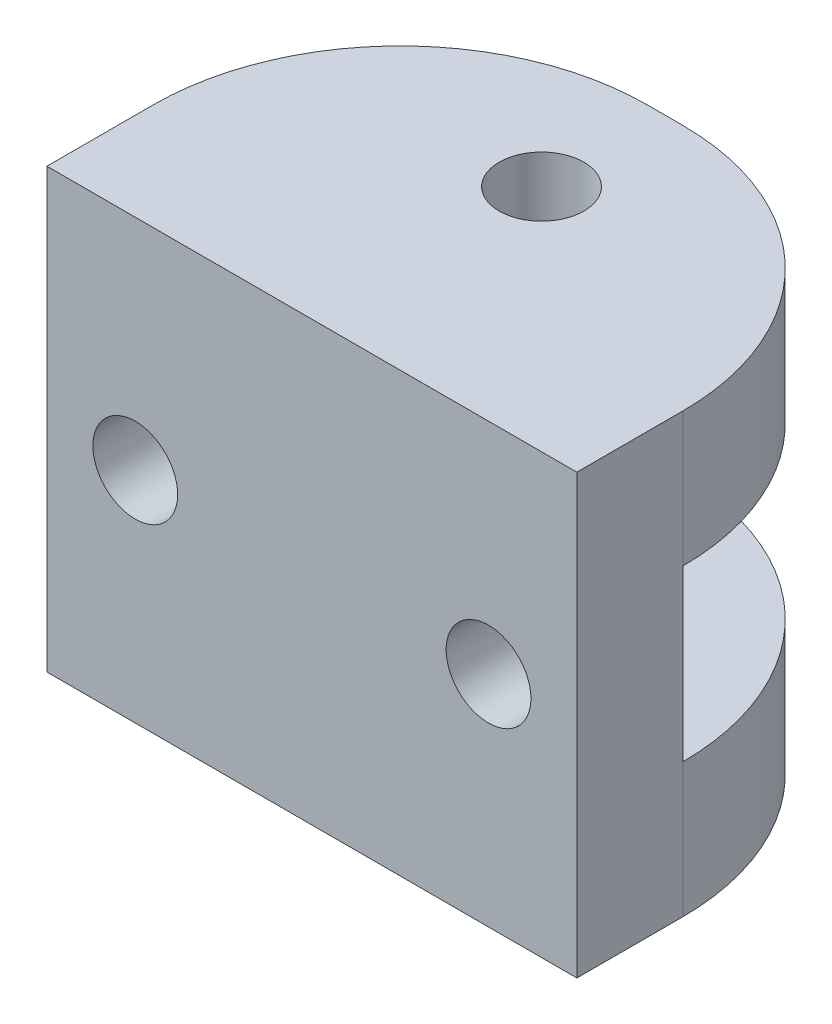
SolidWorks part; units mm, degrees
ref_plane "Front Plane" through (0, 0, 0) normal (0, 0, 1) x (1, 0, 0)
ref_plane "Top Plane" through (0, 0, 0) normal (0, 1, 0) x (1, 0, 0)
ref_plane "Right Plane" through (0, 0, 0) normal (1, 0, 0) x (0, 0, -1)
sketch "Sketch1" plane through (0, 0, 0) normal (1, 0, 0) x (0, 0, -1)
  line L0 (50, 62) -> (50, 43)
  line L1 (0, 0) -> (50, 0)
  line L2 (0, 0) -> (0, 62)
  line L3 (0, 62) -> (50, 62)
  line L5 (50, 43) -> (15, 43)
  line L6 (15, 43) -> (15, 19)
  line L7 (15, 19) -> (50, 19)
  line L8 (50, 19) -> (50, 0)
  dimension "D1" = 24
  dimension "D2" = 62
  dimension "D3" = 35
  dimension "D4" = 50
extrude "Boss-Extrude1" add sketch "Sketch1" along normal blind 75
sketch "Sketch2" plane through (0, 0, 0) normal (0, 0, 1) x (1, 0, 0)
  line L0 (0, 31) -> (75, 31) construction
  line L1 (0, 62) -> (0, 0) construction
  line L2 (75, 62) -> (75, 0) construction
  circle A0 centre (62.5, 31) radius 6
  circle A1 centre (12.5, 31) radius 6
  point P10 (37.5, 31)
  dimension "D3" = 12
  dimension "D1" = 50
  dimension "D2" = 25
extrude "Cut-Extrude1" cut sketch "Sketch2" against normal through all
sketch "Sketch3" plane through (0, 62, 0) normal (0, 1, 0) x (1, 0, 0)
  line L0 (0, 32.5) -> (75, 32.5) construction
  line L1 (0, 50) -> (0, 0) construction
  line L2 (75, 50) -> (75, 0) construction
  line L3 (75, 50) -> (0, 50) construction
  circle A0 centre (37.5, 32.5) radius 6
  dimension "D2" = 12
  dimension "D1" = 17.5
extrude "Cut-Extrude2" cut sketch "Sketch3" against normal through all
fillet "Fillet1" radius 35 4 edges at (75, 9.5, -50) (0, 9.5, -50) (0, 52.5, -50) (75, 52.5, -50)
equation "\"mbtOD\" = 850"
equation "\"mbtT\" = 6"
equation "\"mbtL\" = 1500"
equation "\"mbtFlangeOD\" = 950"
equation "\"mbtFlangeT\" = 12"
equation "\"mbtFlangeBoltCircleDia\" = 650"
equation "\"mbtFlangeHoleDia\" = 12"
equation "\"mbtOringSize\" = 10 "
equation "\"mbtOringDia\" = 620"
equation "\"mbtWidth\" = 2250"
equation "\"skiWidth\" = 1250"
equation "\"D1@Sketch1\"=\"mbtFlangeT\"+12mm"
equation "\"D2@Sketch1\"=\"mbtFlangeT\"+50mm"
